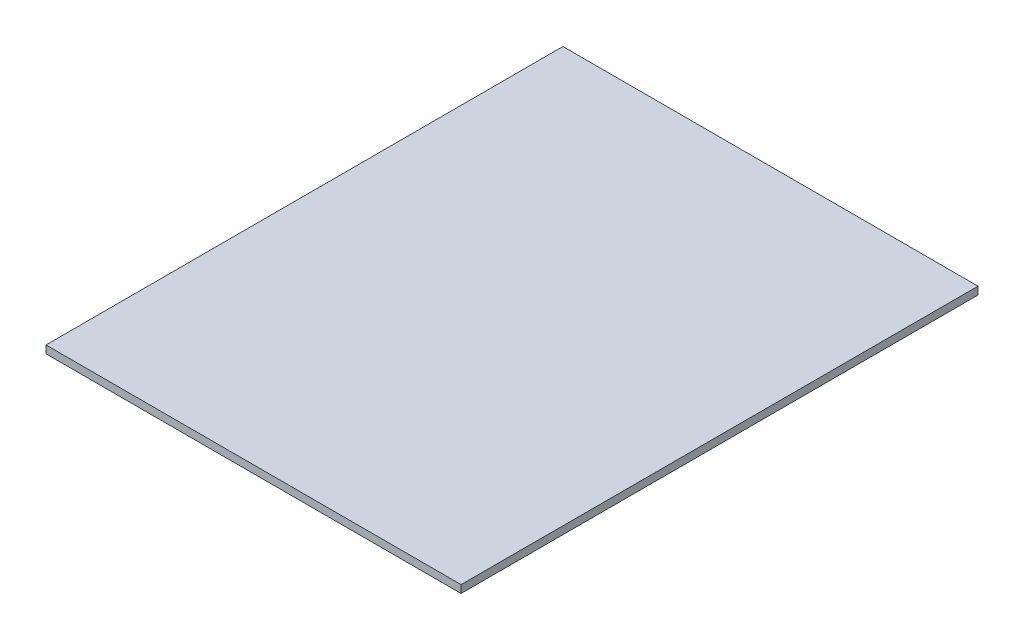
SolidWorks part; units mm, degrees
ref_plane "Front Plane" through (0, 0, 0) normal (0, 0, 1) x (1, 0, 0)
ref_plane "Top Plane" through (0, 0, 0) normal (0, 1, 0) x (1, 0, 0)
ref_plane "Right Plane" through (0, 0, 0) normal (1, 0, 0) x (0, 0, -1)
sketch "Sketch1" plane through (0, 0, 0) normal (0, 1, 0) x (1, 0, 0)
  line L1 (0, 0) -> (93.95, 0)
  line L2 (0, 0) -> (0, 117)
  line L3 (0, 117) -> (93.95, 117)
  line L4 (93.95, 0) -> (93.95, 117)
  dimension "D1" = 117
  dimension "D2" = 93.95
extrude "Boss-Extrude1" add sketch "Sketch1" along normal blind 1.74
